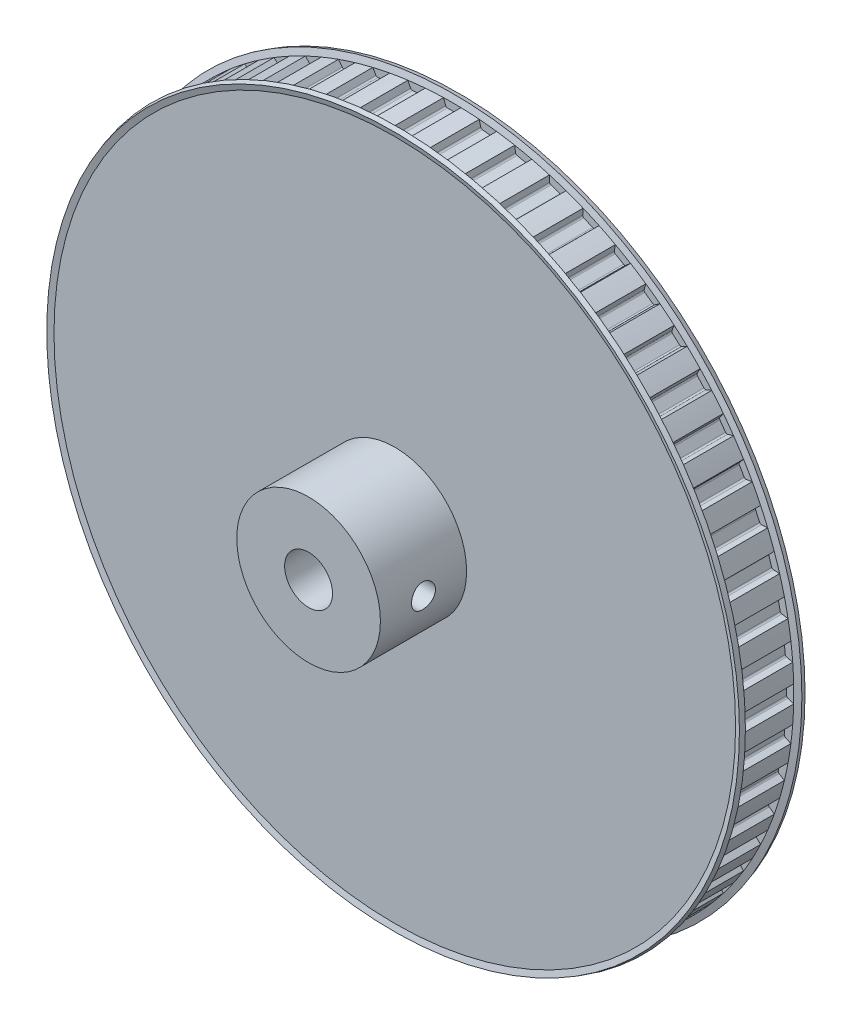
SolidWorks part; units mm, degrees
material "6061-T6 (SS)"
ref_plane "Plane1" through (0, 0, 0) normal (0, 0, 1) x (1, 0, 0)
ref_plane "Plane2" through (0, 0, 0) normal (0, 1, 0) x (1, 0, 0)
ref_plane "Plane3" through (0, 0, 0) normal (1, 0, 0) x (0, 0, -1)
sketch "Clipboard" plane through (0, 0, 0) normal (0, 0, 1) x (1, 0, 0)
  line L0 (0, 0) -> (14.224, 0)
  line L1 (0, 0) -> (19.05, 32.9956)
  line L2 (0, 0) -> (19.05, -32.9956)
  dimension "Overall_len" = 38.1
  dimension "T_dim" = 14.224
  dimension "OAL" = 38.1
  dimension "Show_grvs" = 60
  dimension "Num_grvs" = 60
sketch "Sketch1" plane through (0, 0, 0) normal (0, 0, 1) x (1, 0, 0)
  circle A0 centre (0, 0) radius 90.5764
  dimension "Outside_dia" = 181.1528
extrude "BasePulley" add sketch "Sketch1" against normal blind 13.97
sketch "Sketch2" plane through (0, 0, 0) normal (1, 0, 0) x (0, 0, -1)
  line L0 (13.97, 90.5764) -> (14.4748, 92.2274)
  line L1 (14.4748, 92.2274) -> (15.6893, 91.8561)
  line L2 (6.985, 0) -> (6.985, 66.675) construction
  line L3 (15.6893, 91.8561) -> (15.24, 90.3866)
  line L4 (15.24, 90.3866) -> (15.24, 0)
  line L5 (0, 90.5764) -> (-0.5048, 92.2274)
  line L6 (13.97, -90.5764) -> (13.97, 90.5764) construction
  line L7 (-0.5048, 92.2274) -> (-1.7193, 91.8561)
  line L8 (-1.7193, 91.8561) -> (-1.27, 90.3866)
  line L9 (-1.27, 90.3866) -> (-1.27, 0)
  line L10 (13.97, 90.5764) -> (0, 90.5764)
  line L11 (0, 0) -> (38.2092, 0) construction
  line L12 (13.97, 0) -> (0, 0) construction
  line L13 (-1.27, 0) -> (15.24, 0)
  dimension "D1" = 6.985
  dimension "Flange_ang" = 17
  dimension "Flange_thickness" = 1.27
  dimension "D2" = 90.5764
  dimension "Flange_ht" = 1.651
  dimension "D3" = 1.27
revolve "Flange" add sketch "Sketch2" angle 360 about L11
ref_plane "Plane4" through (0, 0, -6.985) normal (0, 0, 1) x (1, 0, 0)
sketch "Sketch3" plane through (0, 0, -6.985) normal (0, 0, 1) x (1, 0, 0)
  line L0 (-2.3241, 90.5764) -> (-2.3241, 115.9764)
  line L1 (2.3241, 90.5764) -> (2.3241, 115.9764)
  line L2 (0, 0) -> (0, 90.5764) construction
  line L3 (-2.3241, 90.5764) -> (2.3241, 90.5764) construction
  line L4 (-1.275, 88.6714) -> (1.275, 88.6714)
  line L5 (2.3241, 90.5764) -> (1.7524, 89.0057)
  line L6 (-2.3241, 90.5764) -> (-1.7524, 89.0057)
  line L7 (2.3241, 115.9764) -> (-2.3241, 115.9764)
  arc A0 (1.275, 88.6714) -> (1.7524, 89.0057) centre (1.275, 89.1794) ccw
  arc A2 (-1.7524, 89.0057) -> (-1.275, 88.6714) centre (-1.275, 89.1794) ccw
  dimension "Grv_rad_bot" = 0.508
  dimension "D4" = 25.4
  dimension "D1" = 90.5764
  dimension "Grv_ang" = 40
  dimension "Grv_width" = 4.6482
  dimension "D3" = 20
  dimension "Grv_depth" = 1.905
extrude "Groove" cut sketch "Sketch3" against normal mid plane 13.97
pattern_circular "Grooves" count 60 every 6 about axis through (0, 0, -13.97) along (0, 0, 1) of "Groove"
sketch "Sketch4" plane through (0, 0, 0) normal (1, 0, 0) x (0, 0, -1)
  line L0 (0, 0) -> (47.6781, 0) construction
  line L1 (13.97, 0) -> (0, 0) construction
  line L2 (0, 0) -> (-24.13, 0)
  line L3 (-24.13, 0) -> (-24.13, 19.05)
  line L4 (-24.13, 19.05) -> (0, 19.05)
  line L5 (0, 19.05) -> (0, 0)
  line L6 (-24.13, -19.05) -> (0, -19.05) construction
  dimension "Hub_dia" = 38.1
  dimension "Hub_depth" = 24.13
revolve "BaseHub" add sketch "Sketch4" angle 360 about L0
sketch "BorSke" plane through (0, 0, 24.13) normal (0, 0, 1) x (1, 0, 0)
  circle A0 centre (0, 0) radius 6.35
  dimension "Diameter" = 12.7
extrude "Bore" cut sketch "BorSke" against normal through all
sketch "KeySke" plane through (0, 0, 24.13) normal (0, 0, 1) x (1, 0, 0)
  line L0 (1.5875, 7.874) -> (1.5875, 0)
  line L1 (1.5875, 7.874) -> (-1.5875, 7.874)
  line L2 (-1.5875, 7.874) -> (-1.5875, 0)
  line L3 (-1.5875, 0) -> (1.5875, 0)
  line L4 (0, 31.75) -> (0, -3.175) construction
  dimension "Width" = 3.175
  dimension "Offset" = 7.874
extrude "Keyway" [suppressed] cut sketch "KeySke" against normal through all
pattern_circular "Keyway2" [suppressed] count 2 every 90
sketch "Sketch5" plane through (0, 0, 0) normal (1, 0, 0) x (0, 0, -1)
  line L0 (-24.13, 0) -> (-1.27, 0) construction
  line L1 (-24.13, 19.05) -> (-24.13, -19.05) construction
  line L2 (-1.27, 19.05) -> (-1.27, -19.05) construction
  circle A0 centre (-12.7, 0) radius 3.175
  dimension "D1" = 6.35
extrude "Cut-Extrude1" cut sketch "Sketch5" against normal through all and the other way through all
equation "\"D1@Plane4\" = \"Width@BasePulley\" / 2"
equation "\"D1@Groove\" = \"Width@BasePulley\""
equation "\"D1@Sketch3\" = \"Outside_dia@Sketch1\" / 2"
equation "\"D1@Sketch2\" = \"Width@BasePulley\" / 2"
equation "\"D2@Sketch2\" = \"Outside_dia@Sketch1\" / 2"
equation "\"D3@Sketch2\" = \"Flange_thickness@Sketch2\""
equation "\"Num_grvs@Clipboard\" = int( \"Num_grvs@Clipboard\" )"
equation "\"Show_grvs@Clipboard\" = int( \"Show_grvs@Clipboard\" )"
equation "\"Show_grvs@Clipboard\" = ((sgn( \"Show_grvs@Clipboard\" - \"Num_grvs@Clipboard\" )-1)*( \"Show_grvs@Clipboard\" - \"Num_grvs@Clipboard\" ))/-2+ \"Num_grvs@Clipboard\""
equation "\"Show_grvs@Clipboard\" = ((sgn( \"Show_grvs@Clipboard\" - 1.0)+1)*( \"Show_grvs@Clipboard\" - 1.0))/2 +1.0"
equation "\"Angle@Grooves\" = 360.0 / \"Num_grvs@Clipboard\""
equation "\"Num_grvs@Grooves\" =  \"Show_grvs@Clipboard\""
equation "\"Offset@KeySke\" = \"T_dim@Clipboard\" - \"Diameter@BorSke\" / 2.0"
equation "\"OAL@Clipboard\" = \"Overall_len@Clipboard\""
equation "\"Hub_depth@Sketch4\" = \"OAL@Clipboard\" - \"Width@BasePulley\""
